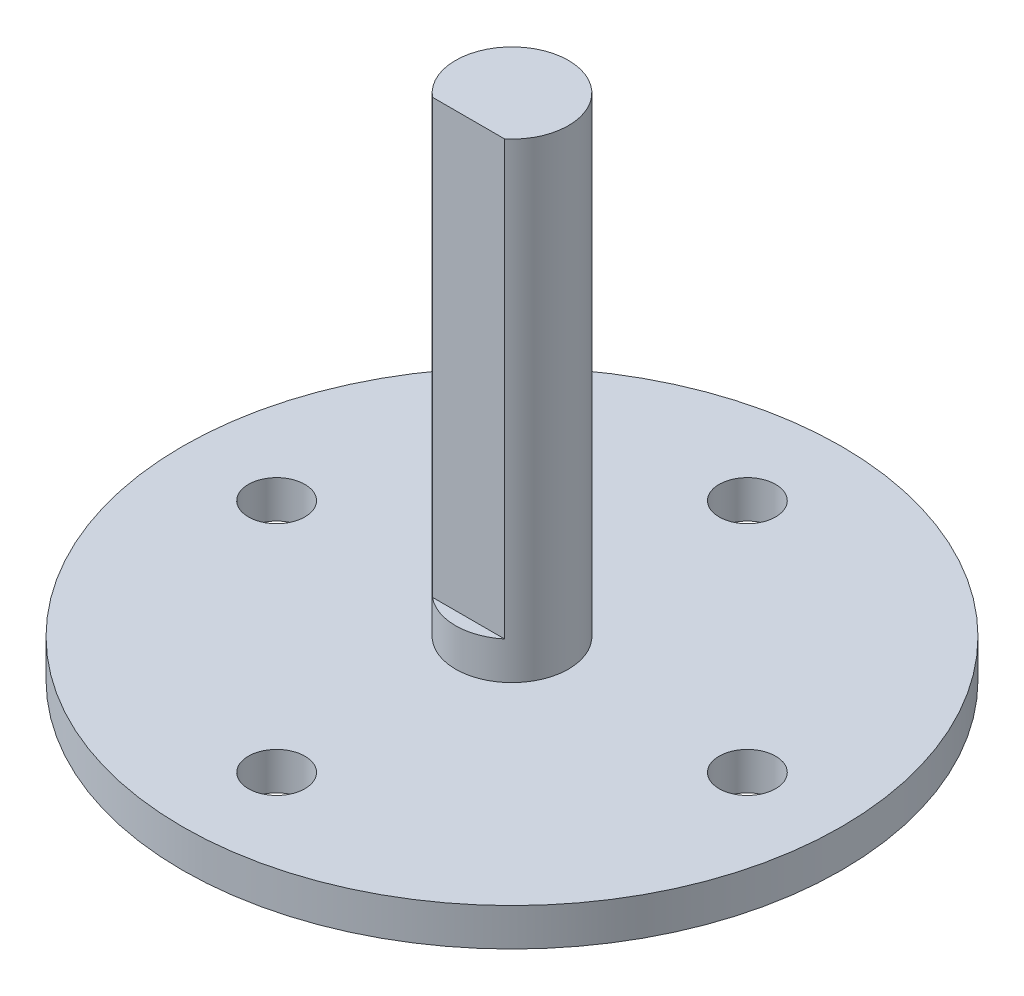
SolidWorks part; units mm, degrees
ref_plane "前视基准面" through (0, 0, 0) normal (0, 0, 1) x (1, 0, 0)
ref_plane "上视基准面" through (0, 0, 0) normal (0, 1, 0) x (1, 0, 0)
ref_plane "右视基准面" through (0, 0, 0) normal (1, 0, 0) x (0, 0, -1)
other "Configuration Table"
sketch "草图1" plane through (0, 0, 0) normal (0, 1, 0) x (1, 0, 0)
  circle A0 centre (0, 0) radius 12.5 construction
  circle A1 centre (0, 12.5) radius 1.5
  circle A2 centre (12.5, 0) radius 1.5
  circle A3 centre (0, -12.5) radius 1.5
  circle A4 centre (-12.5, 0) radius 1.5
  circle A6 centre (0, 0) radius 17.5
  point P14 (0, 0)
  dimension "D1" = 25
  dimension "D2" = 3
  dimension "D3" = 4
  dimension "D5" = 35
extrude "凸台-拉伸1" add sketch "草图1" along normal blind 2
sketch "草图2" plane through (0, 2, 0) normal (0, 1, 0) x (1, 0, 0)
  line L0 (-1.9167, -2.3079) -> (1.9167, -2.3079)
  arc A0 (1.9167, -2.3079) -> (-1.9167, -2.3079) centre (0, 0) ccw
  dimension "D1" = 6
extrude "凸台-拉伸2" add sketch "草图2" along normal blind 25
sketch "草图3" plane through (0, 2, 0) normal (0, 1, 0) x (1, 0, 0)
  circle A0 centre (0, 0) radius 3
extrude "凸台-拉伸3" add sketch "草图3" along normal blind 2
